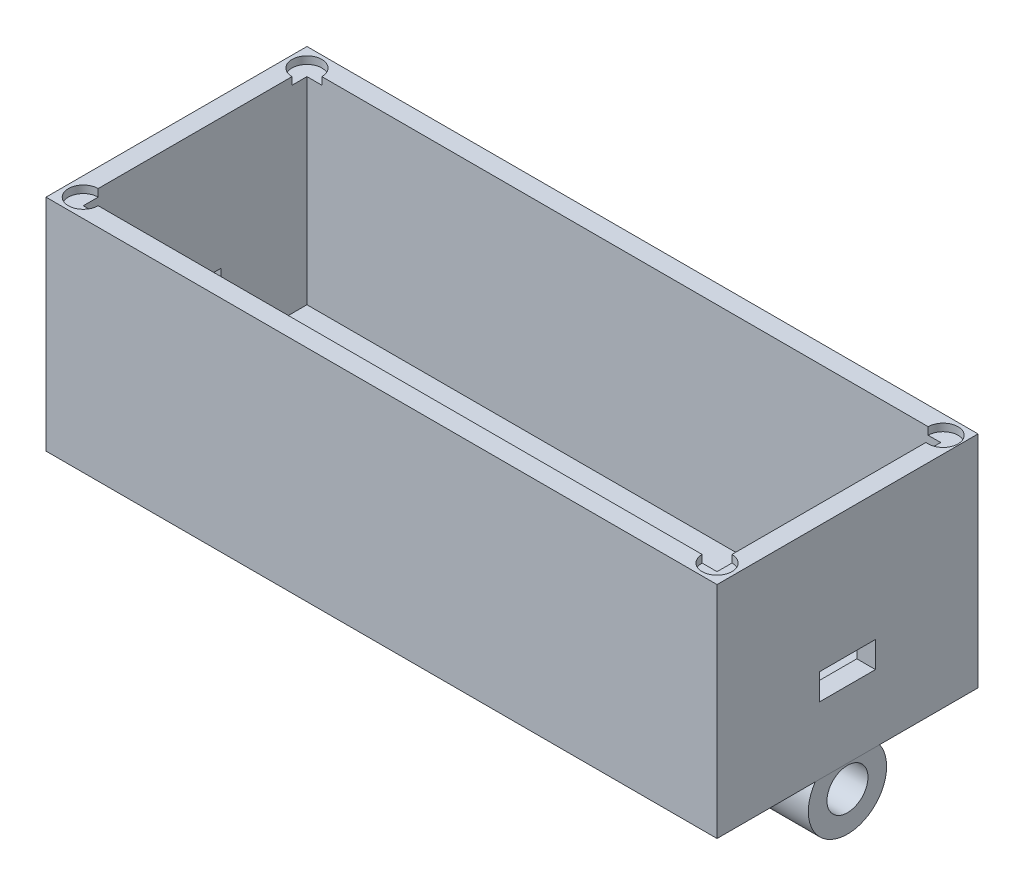
SolidWorks part; units mm, degrees
ref_plane "Front Plane" through (0, 0, 0) normal (0, 0, 1) x (1, 0, 0)
ref_plane "Top Plane" through (0, 0, 0) normal (0, 1, 0) x (1, 0, 0)
ref_plane "Right Plane" through (0, 0, 0) normal (1, 0, 0) x (0, 0, -1)
sketch "Sketch2" plane through (0, 0, 0) normal (1, 0, 0) x (0, 0, -1)
  circle A0 centre (0, 0) radius 5.5
  circle A1 centre (0, 0) radius 10.5
  dimension "D1" = 5
extrude "Boss-Extrude1" add sketch "Sketch2" along normal blind 180
ref_plane "Plane1" through (0, 10, 0) normal (0, 1, 0) x (1, 0, 0)
sketch "Sketch6" plane through (0, 10, 0) normal (0, 1, 0) x (1, 0, 0)
  line L0 (-22.2287, 0) -> (202.256, 0) construction
  line L1 (90.0136, 0) -> (90.0136, -39.321) construction
  line L2 (90.0136, 0) -> (90.0136, 42.393) construction
  line L4 (0.0136, -35) -> (180.0136, -35)
  line L5 (0.0136, -35) -> (0.0136, 35)
  line L6 (0.0136, 35) -> (180.0136, 35)
  line L7 (180.0136, -35) -> (180.0136, 35)
  line L8 (0.0136, -35) -> (180.0136, 35) construction
  line L9 (0.0136, 35) -> (180.0136, -35) construction
  point P10 (90.0136, 0)
  point P11 (90.4857, 0)
  point P12 (90.6563, 0)
  point P13 (0, 0)
  point P14 (0, 0)
  point P15 (88.976, 0)
  point P16 (90.0136, 0)
  dimension "D1" = 70
  dimension "D2" = 180
extrude "Boss-Extrude2" add sketch "Sketch6" against normal blind 4
sketch "Sketch8" plane through (0, 10, 0) normal (0, 1, 0) x (1, 0, 0)
  line L13 (0.0136, 35) -> (180.0136, 35)
  line L14 (0.0136, 35) -> (0.0136, -35)
  line L15 (0.0136, -35) -> (180.0136, -35)
  line L24 (5.0136, -30) -> (175.0136, -30)
  line L25 (175.0136, -30) -> (175.0136, 30)
  line L26 (175.0136, 30) -> (5.0136, 30)
  line L27 (5.0136, 30) -> (5.0136, -30)
  line L28 (5.0136, -30) -> (175.0136, -30)
  line L29 (175.0136, -30) -> (175.0136, 30)
  line L30 (175.0136, 30) -> (5.0136, 30)
  line L31 (5.0136, 30) -> (5.0136, -30)
  line L32 (180.0136, 35) -> (180.0136, -35)
  line L33 (0.0136, 35) -> (180.0136, -35) construction
  line L34 (0.0136, -35) -> (180.0136, 35) construction
  point P4 (90.0136, 0)
  dimension "D2" = 5
extrude "Boss-Extrude3" add sketch "Sketch8" along normal blind 55
sketch "Sketch9" plane through (180.0136, 0, 0) normal (1, 0, 0) x (0, 0, -1)
  line L0 (11.55, 10) -> (-11.55, 10) construction
  line L1 (-7.5, 24) -> (7.5, 24)
  line L2 (-7.5, 24) -> (-7.5, 31)
  line L3 (-7.5, 31) -> (7.5, 31)
  line L4 (7.5, 24) -> (7.5, 31)
  line L5 (-7.5, 24) -> (7.5, 31) construction
  line L6 (-7.5, 31) -> (7.5, 24) construction
  point P0 (0, 27.5)
  point P5 (0, 15.527)
  dimension "D1" = 7
  dimension "D2" = 15
  dimension "D3" = 14
extrude "Cut-Extrude1" cut sketch "Sketch9" against normal blind 5
sketch "Sketch10" plane through (0.0136, 0, 0) normal (-1, 0, 0) x (0, 0, 1)
  line L0 (11.55, 10) -> (-11.55, 10) construction
  line L1 (-7, 22) -> (7, 22)
  line L2 (-7, 22) -> (-7, 30)
  line L3 (-7, 30) -> (7, 30)
  line L4 (7, 22) -> (7, 30)
  line L5 (-7, 22) -> (7, 30) construction
  line L6 (-7, 30) -> (7, 22) construction
  point P0 (0, 26)
  point P5 (0, 15.2239)
  point P6 (0, 18.5588)
  dimension "D1" = 14
  dimension "D2" = 8
  dimension "D3" = 12
extrude "Cut-Extrude2" cut sketch "Sketch10" against normal blind 5
sketch "Sketch11" plane through (0, 65, 0) normal (0, 1, 0) x (1, 0, 0)
  line L0 (175.0136, 30) -> (5.0136, 30) construction
  circle A0 centre (5.0136, 30) radius 4
  circle A1 centre (175.6563, 30) radius 4
  circle A2 centre (5.0136, -30) radius 4
  circle A3 centre (175.0136, -30) radius 4
  point P2 (3.5668, 32.1106)
  point P3 (0, 0)
  point P4 (4.7625, 30.796)
  point P5 (5.6563, 30)
  point P13 (5.6563, -30)
  point P15 (175.6563, -30)
  point P17 (175.6563, 30)
  point P20 (5.6563, -30)
extrude "Cut-Extrude3" cut sketch "Sketch11" against normal blind 2
